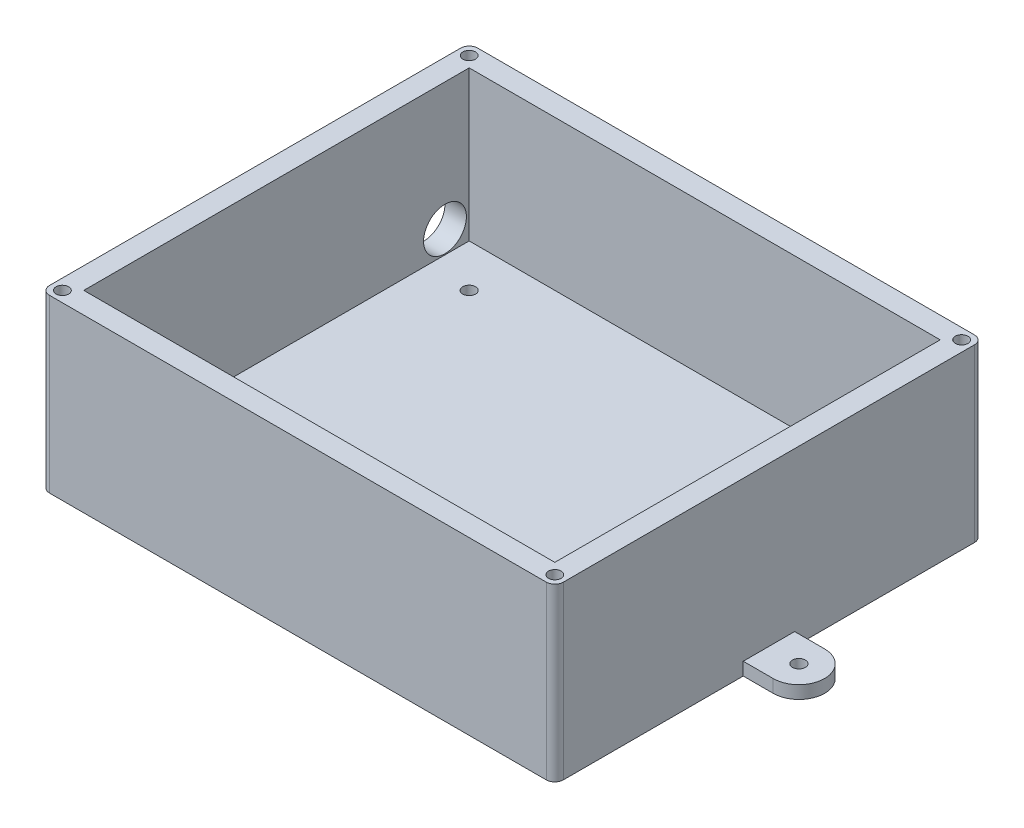
SolidWorks part; units mm, degrees
ref_plane "Front Plane" through (0, 0, 0) normal (0, 0, 1) x (1, 0, 0)
ref_plane "Top Plane" through (0, 0, 0) normal (0, 1, 0) x (1, 0, 0)
ref_plane "Right Plane" through (0, 0, 0) normal (1, 0, 0) x (0, 0, -1)
sketch "Sketch1" plane through (0, 0, 0) normal (0, 1, 0) x (1, 0, 0)
  line L1 (-60, 50) -> (60, 50)
  line L2 (-60, 50) -> (-60, -50)
  line L3 (-60, -50) -> (60, -50)
  line L4 (60, 50) -> (60, -50)
  line L5 (-60, 50) -> (60, -50) construction
  line L6 (-60, -50) -> (60, 50) construction
  point P0 (0, 0)
extrude "Boss-Extrude1" add sketch "Sketch1" along normal blind 40
shell "Shell1" thickness 5
sketch "Sketch2" plane through (0, 5, 0) normal (0, 1, 0) x (1, 0, 0)
  line L0 (0, 0) -> (-55, 0) construction
  line L1 (-55, 45) -> (-55, -45) construction
  line L2 (0, 0) -> (55, 0) construction
  line L3 (55, -45) -> (55, 45) construction
  line L4 (0, -45) -> (0, 45) construction
  line L5 (-55, -45) -> (55, -45) construction
  line L6 (55, 45) -> (-55, 45) construction
  circle A0 centre (-45, 35) radius 1.5
  circle A1 centre (45, 35) radius 1.5
  circle A2 centre (45, -35) radius 1.5
  circle A3 centre (-45, -35) radius 1.5
  dimension "D1" = 3
  dimension "D3" = 45
  dimension "D2" = 35
extrude "Cut-Extrude1" cut sketch "Sketch2" against normal through all
sketch "Sketch4" plane through (0, 0, 0) normal (0, -1, 0) x (1, 0, 0)
  line L0 (-60, 0) -> (60, 0) construction
  line L1 (-60, -50) -> (-60, 50) construction
  line L2 (60, 50) -> (60, -50) construction
  line L3 (63.5, 6) -> (63.5, -6) construction
  line L4 (60, 6) -> (67, 6)
  line L5 (60, 6) -> (60, -6)
  line L6 (60, -6) -> (67, -6)
  line L8 (70, 0) -> (60, 0) construction
  line L9 (0, -50) -> (0, 50) construction
  line L12 (60, -50) -> (-60, -50) construction
  line L13 (-60, 50) -> (60, 50) construction
  line L14 (-60, 6) -> (-60, -6)
  line L15 (-60, -6) -> (-67, -6)
  line L16 (-60, 6) -> (-67, 6)
  arc A0 (67, 6) -> (67, -6) centre (67, 0) cw
  circle A1 centre (67, 0) radius 1.5
  circle A2 centre (-67, 0) radius 1.5
  arc A3 (-67, 6) -> (-67, -6) centre (-67, 0) ccw
  dimension "D3" = 3
  dimension "D4" = 12
  dimension "D2" = 6
  dimension "D1" = 7
extrude "Boss-Extrude2" add sketch "Sketch4" against normal blind 3
sketch "Sketch5" plane through (0, 40, 0) normal (0, 1, 0) x (1, 0, 0)
  line L0 (-60, 50) -> (-55, 45) construction
  line L1 (-60, -50) -> (-55, -45) construction
  line L2 (-57.5, 47.5) -> (-57.5, -47.5) construction
sketch "Sketch7" plane through (-60, 0, 0) normal (-1, 0, 0) x (0, 0, 1)
  circle A0 centre (-39.3491, 10.2495) radius 5
  point P2 (-38.059, 11.2171)
  point P3 (-39.3491, 10.2495)
  dimension "D1" = 10
extrude "Cut-Extrude2" cut sketch "Sketch7" against normal up to surface (5 mm away) up to face at (-55, 22.5, 0)
sketch "Sketch8" plane through (0, 40, 0) normal (0, 1, 0) x (1, 0, 0)
  circle A0 centre (-57.5, 47.5) radius 1.475
  dimension "D1" = 2.95
extrude "Cut-Extrude3" cut sketch "Sketch8" against normal blind 10
mirror "Mirror1" about plane through (0, 0, 0) normal (1, 0, 0) of "Cut-Extrude3"
mirror "Mirror2" about plane through (0, 0, 0) normal (0, 0, 1) of "Mirror1", "Cut-Extrude3"
fillet "Fillet1" radius 2 4 edges at (60, 20, 50) (60, 20, -50) (-60, 20, 50) (-60, 20, -50)
